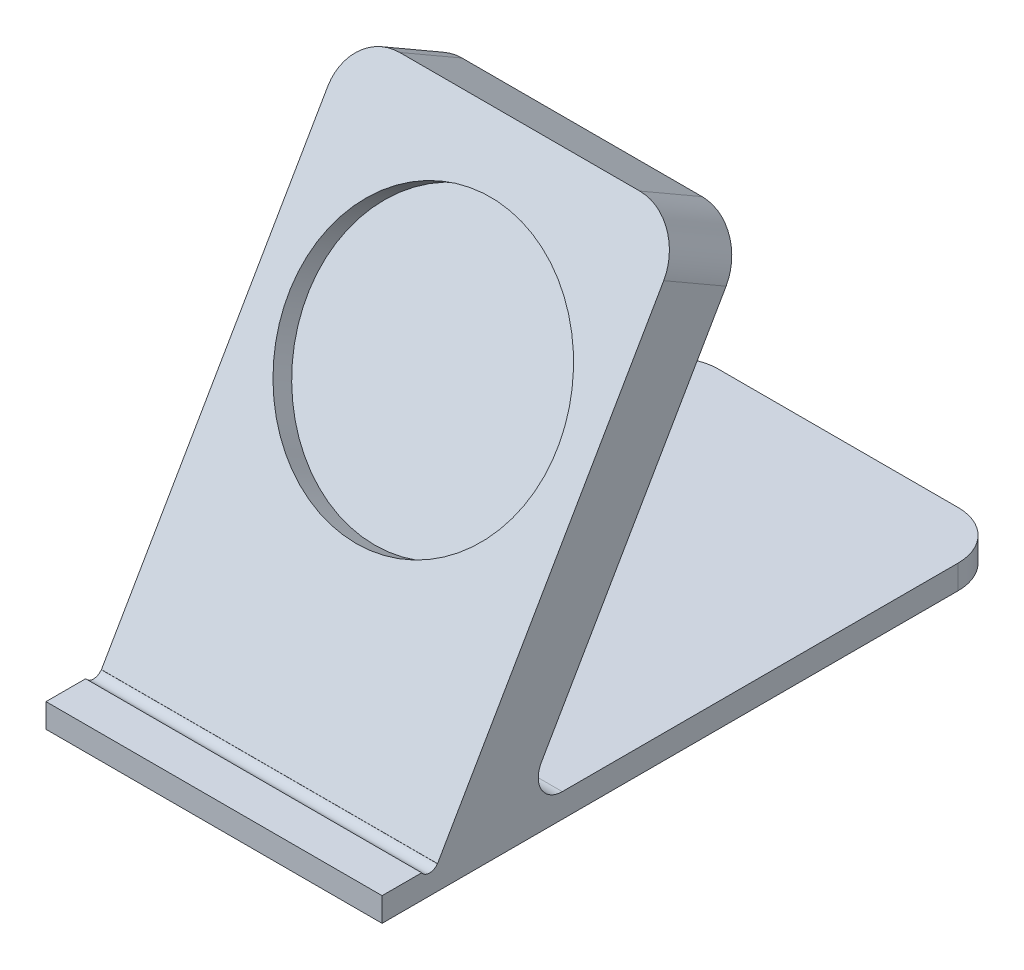
SolidWorks part; units mm, degrees
ref_plane "前视基准面" through (0, 0, 0) normal (0, 0, 1) x (1, 0, 0)
ref_plane "上视基准面" through (0, 0, 0) normal (0, 1, 0) x (1, 0, 0)
ref_plane "右视基准面" through (0, 0, 0) normal (1, 0, 0) x (0, 0, -1)
sketch "草图1" plane through (0, 0, 0) normal (0, 1, 0) x (1, 0, 0)
  line L1 (-25, 65) -> (25, 65)
  line L2 (-35, 55) -> (-35, -65)
  line L3 (-35, -65) -> (35, -65)
  line L4 (35, 55) -> (35, -65)
  line L5 (-35, 65) -> (35, -65) construction
  line L6 (-35, -65) -> (35, 65) construction
  arc A0 (25, 65) -> (35, 55) centre (25, 55) cw
  arc A1 (-25, 65) -> (-35, 55) centre (-25, 55) ccw
  point P0 (0, 0)
  dimension "D1" = 130
  dimension "D3" = 10
  dimension "D2" = 70
extrude "凸台-拉伸1" add sketch "草图1" along normal blind 5
ref_plane "基准面1" through (0, 29.3958, 50.9151) normal (0, 0.5, 0.866) x (1, 0, 0)
ref_plane "基准面2" through (0, 29.3958, 50.9151) normal (0, 0.5, 0.866) x (1, 0, 0)
ref_plane "基准面3" through (0, 24.3958, 42.2548) normal (0, 0.5, 0.866) x (1, 0, 0)
sketch "草图8" plane through (0, 24.3958, 42.2548) normal (0, 0.5, 0.866) x (1, 0, 0)
  line L0 (-35, -28.1699) -> (35, -28.1699) construction
  line L1 (-35, -28.1699) -> (35, -28.1699)
  line L3 (-35, -28.1699) -> (35, -28.1699)
  line L4 (-35, -28.1699) -> (-35, 71.8301)
  line L5 (-25, 81.8301) -> (25, 81.8301)
  line L6 (35, -28.1699) -> (35, 71.8301)
  arc A0 (-35, 71.8301) -> (-25, 81.8301) centre (-25, 71.8301) cw
  arc A1 (25, 81.8301) -> (35, 71.8301) centre (25, 71.8301) cw
  point P7 (-35, 81.8301)
  dimension "D3" = 10
  dimension "D1" = 110
  dimension "D2" = 70
extrude "凸台-拉伸3" add sketch "草图8" against normal blind 15 contours A1 L5 A0 L4 L1 L6
sketch "草图9" plane through (0, 0, 65) normal (0, 0, 1) x (1, 0, 0)
  line L1 (-35, 0) -> (84.6416, 0)
  line L2 (-35, 0) -> (-35, -10.2869)
  line L3 (-35, -10.2869) -> (84.6416, -10.2869)
  line L4 (84.6416, 0) -> (84.6416, -10.2869)
extrude "切除-拉伸2" cut sketch "草图9" against normal through all
sketch "草图10" plane through (-35, 0, 0) normal (-1, 0, 0) x (0, 0, 1)
  circle A0 centre (55.1167, 6.1236) radius 1.9829
  point P2 (57.0675, 4.5037)
extrude "切除-拉伸3" cut sketch "草图10" against normal through all contours A0
sketch "草图13" plane through (35, 0, 0) normal (1, 0, 0) x (0, 0, -1)
  line L0 (-36.1325, 5) -> (6.6506, 79.1025) construction
  line L1 (-36.1325, 5) -> (-31.8024, 12.5)
  line L2 (-36.1325, 5) -> (55, 5) construction
  line L3 (-36.1325, 5) -> (-27.4722, 5)
  circle A0 centre (-27.4722, 10) radius 5
  line M8 (55, 5) -> (-36.1325, 5)
  line M9 (-36.1325, 5) -> (6.6506, 79.1025)
  dimension "D1" = 10
extrude "凸台-拉伸5" add sketch "草图13" against normal up to surface (70 mm away) contours A0 M9 M8 up to face at (-35, 19.4846, 21.9508)
sketch "草图14" plane through (0, 24.3958, 42.2548) normal (0, 0.5, 0.866) x (1, 0, 0)
  circle A0 centre (0, 41.6637) radius 28
  point P2 (0, 34.6811)
  point P3 (2.2781, 39.805)
  point P4 (0, 0)
  point P6 (0, 41.6637)
  dimension "D1" = 56
extrude "切除-拉伸5" cut sketch "草图14" against normal blind 4.5
